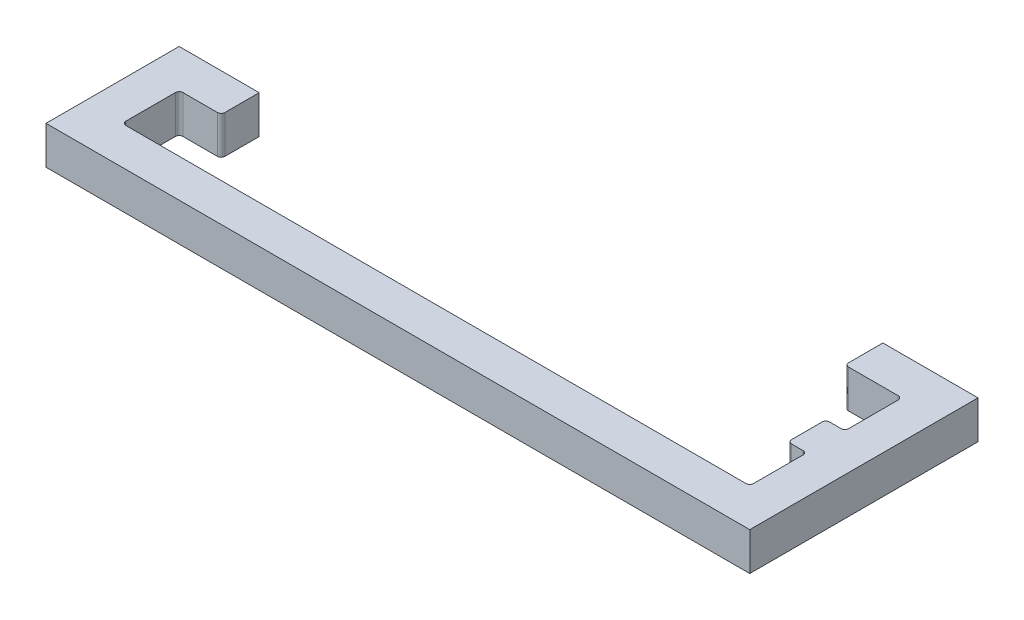
SolidWorks part; units mm, degrees
ref_plane "Front Plane" through (0, 0, 0) normal (0, 0, 1) x (1, 0, 0)
ref_plane "Top Plane" through (0, 0, 0) normal (0, 1, 0) x (1, 0, 0)
ref_plane "Right Plane" through (0, 0, 0) normal (1, 0, 0) x (0, 0, -1)
sketch "Sketch1" plane through (0, 0, 0) normal (0, 1, 0) x (1, 0, 0)
  line L1 (-22.6009, 0.2919) -> (142.3991, 0.2919)
  line L2 (-32.6009, 0.2919) -> (-32.6009, -9.7081)
  line L3 (-32.6009, -9.7081) -> (152.3991, -9.7081)
  line L4 (152.3991, 7.0721) -> (152.3991, -9.7081)
  line L5 (142.3991, 50.2919) -> (152.3991, 50.2919)
  line L6 (142.3991, 40.2919) -> (142.3991, 0.2919)
  line L7 (12.8909, -9.7081) -> (152.3991, -9.7081)
  line L8 (152.3991, 50.2919) -> (152.3991, -9.7081)
  line L9 (-32.6009, 25.2919) -> (-22.6009, 25.2919)
  line L10 (-32.6009, 25.2919) -> (-32.6009, -9.7081)
  line L11 (-32.6009, -9.7081) -> (-14.4864, -9.7081)
  line L12 (-22.6009, 15.2919) -> (-22.6009, 0.2919)
  line L13 (-32.6009, 25.2919) -> (-11.557, 25.2919)
  line L14 (-32.6009, 25.2919) -> (-32.6009, 12.0721)
  line L15 (-22.6009, 15.2919) -> (-11.557, 15.2919)
  line L16 (-11.557, 25.2919) -> (-11.557, 15.2919)
  line L17 (152.3991, 50.2919) -> (127.3991, 50.2919)
  line L18 (152.3991, 50.2919) -> (152.3991, 38.392)
  line L19 (142.3991, 40.2919) -> (127.3991, 40.2919)
  line L20 (127.3991, 50.2919) -> (127.3991, 40.2919)
  line L25 (137.3991, 25.2919) -> (142.3991, 25.2919)
  line L26 (137.3991, 25.2919) -> (137.3991, 15.2919)
  line L27 (137.3991, 15.2919) -> (142.3991, 15.2919)
  line L28 (142.3991, 25.2919) -> (142.3991, 15.2919)
  dimension "D1" = 10
  dimension "D2" = 10
  dimension "D3" = 165
  dimension "D4" = 10
  dimension "D5" = 10
  dimension "D6" = 15
  dimension "D7" = 10
  dimension "D8" = 10
  dimension "D9" = 15
  dimension "D10" = 5
  dimension "D11" = 10
  dimension "D12" = 10
  dimension "D13" = 15
  dimension "D14" = 15
extrude "Boss-Extrude1" add sketch "Sketch1" along normal blind 10 contours L17 L20 L19 L6 L1 L12 L15 L16 L13 L9 L10 L2 L3 L4 L8 L5 | L26 L27 L6 L25
fillet "Fillet3" radius 1 10 edges at (-11.557, 5, -15.2919) (-22.6009, 5, -15.2919) (-22.6009, 5, -0.2919) (142.3991, 5, -0.2919) (142.3991, 5, -15.2919) (137.3991, 5, -15.2919) (137.3991, 5, -25.2919) (142.3991, 5, -25.2919) (142.3991, 5, -40.2919) (127.3991, 5, -40.2919)
